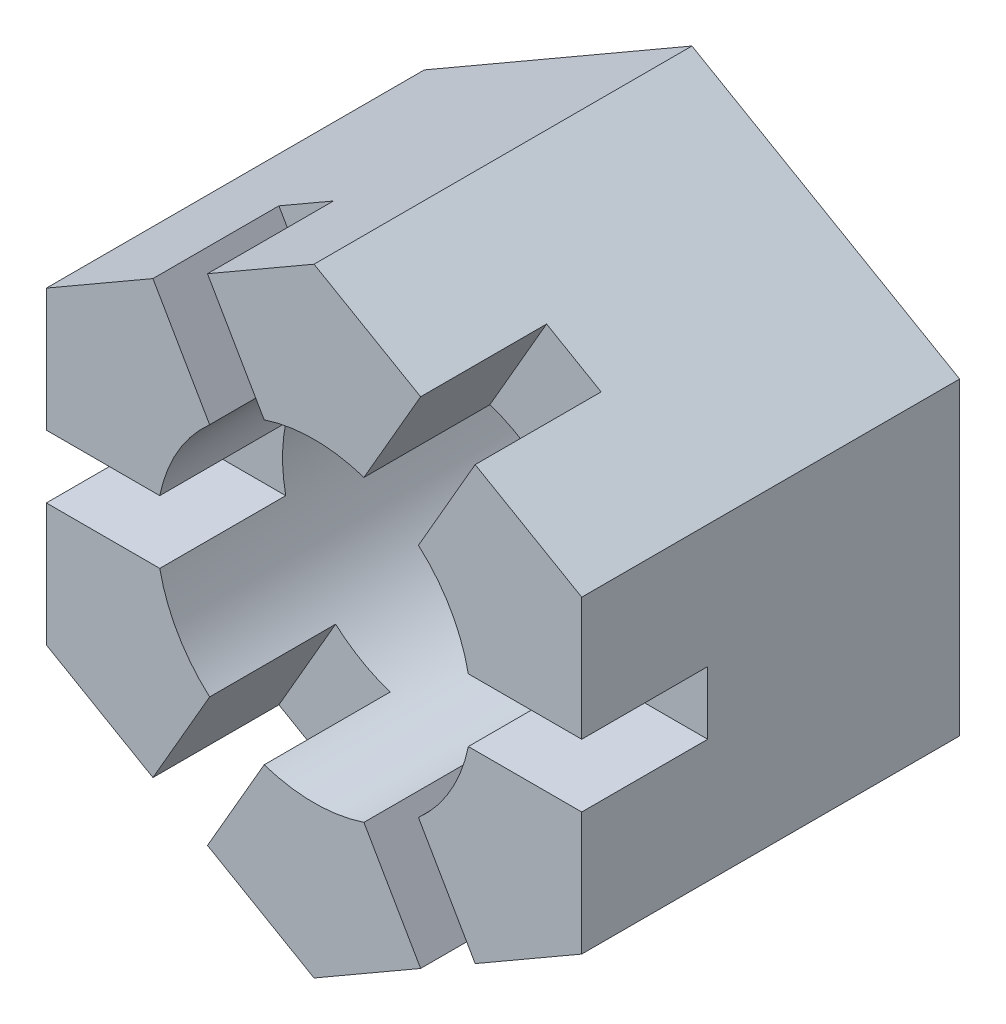
SolidWorks part; units mm, degrees
ref_plane "Plano frontal" through (0, 0, 0) normal (0, 0, 1) x (1, 0, 0)
ref_plane "Plano superior" through (0, 0, 0) normal (0, 1, 0) x (1, 0, 0)
ref_plane "Plano direito" through (0, 0, 0) normal (1, 0, 0) x (0, 0, -1)
sketch "Esboço2" plane through (0, 0, 0) normal (0, 0, 1) x (1, 0, 0)
  line L0 (0, 0) -> (0, 8.3051) construction
  line L1 (0, 9.815) -> (8.5, 4.9075)
  line L2 (0, 9.815) -> (-8.5, 4.9075)
  line L3 (8.5, -4.9075) -> (0, -9.815)
  line L4 (8.5, -4.9075) -> (8.5, 4.9075)
  line L5 (-8.5, -4.9075) -> (-8.5, 4.9075)
  line L6 (-8.5, -4.9075) -> (0, -9.815)
  circle A0 centre (0, 0) radius 5
  point P16 (0, 0)
  point P22 (0, 0)
  point P25 (0, 0)
  dimension "D1" = 10
  dimension "D2" = 120
  dimension "D4" = 17
extrude "Ressalto-extrusão2" add sketch "Esboço2" along normal blind 12
sketch "Esboço3" plane through (8.5, 0, 0) normal (1, 0, 0) x (0, 0, -1)
  line L0 (-12, -4.9075) -> (-12, 4.9075) construction
  line L1 (-8, 1) -> (-12, 1)
  line L2 (-8, 1) -> (-8, -1)
  line L3 (-8, -1) -> (-12, -1)
  line L4 (-12, 1) -> (-12, -1)
  line L5 (-8, 1) -> (-12, -1) construction
  line L6 (-8, -1) -> (-12, 1) construction
  line L7 (0, 0) -> (-10.1212, 0) construction
  point P0 (-10, 0)
  dimension "D1" = 2
  dimension "D2" = 4
extrude "Corte-extrusão1" cut sketch "Esboço3" against normal up to next
pattern_circular "PadrãoCircular1" count 6 every 60 about axis through (0, 0, 0) along (0, 0, 1) of "Corte-extrusão1"
